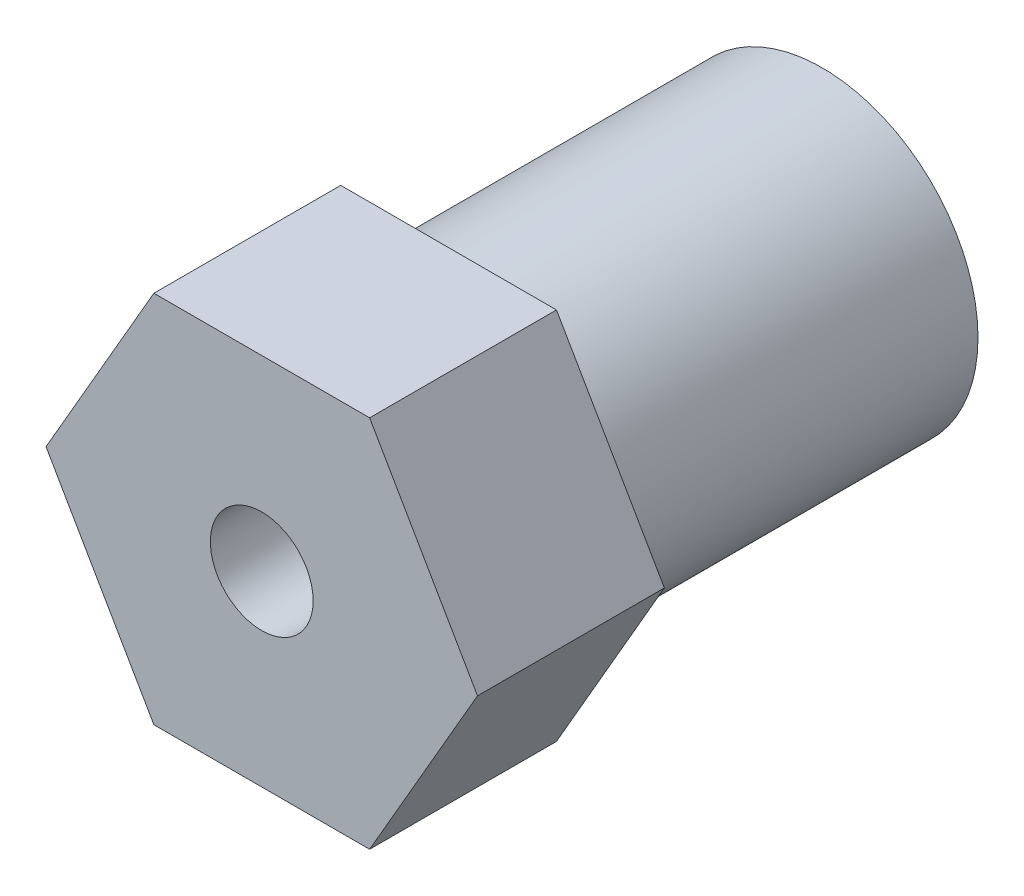
SolidWorks part; units mm, degrees
ref_plane "Front Plane" through (0, 0, 0) normal (0, 0, 1) x (1, 0, 0)
ref_plane "Top Plane" through (0, 0, 0) normal (0, 1, 0) x (1, 0, 0)
ref_plane "Right Plane" through (0, 0, 0) normal (1, 0, 0) x (0, 0, -1)
sketch "Sketch1" plane through (0, 0, 0) normal (0, 0, 1) x (1, 0, 0)
  line L1 (6.9282, 0) -> (3.4641, 6)
  line L2 (3.4641, 6) -> (-3.4641, 6)
  line L3 (-3.4641, 6) -> (-6.9282, 0)
  line L4 (-6.9282, 0) -> (-3.4641, -6)
  line L5 (-3.4641, -6) -> (3.4641, -6)
  line L6 (3.4641, -6) -> (6.9282, 0)
  circle A0 centre (0, 0) radius 6 construction
extrude "Boss-Extrude1" add sketch "Sketch1" along normal blind 6
sketch "Sketch2" plane through (0, 0, 0) normal (0, 0, 1) x (1, 0, 0)
  circle A0 centre (0, 0) radius 5
extrude "Boss-Extrude2" add sketch "Sketch2" against normal blind 12
sketch "Sketch3" plane through (0, 0, 0) normal (0, 0, 1) x (1, 0, 0)
  circle A0 centre (0, 0) radius 2.5
extrude "Cut-Extrude1" cut sketch "Sketch3" against normal blind 12
sketch "Sketch4" plane through (0, 0, 0) normal (0, 0, 1) x (1, 0, 0)
  circle A0 centre (0, 0) radius 1.65
extrude "Cut-Extrude2" cut sketch "Sketch4" along normal blind 6
sketch "Sketch5" plane through (0, 0, 0) normal (0, 1, 0) x (1, 0, 0)
  circle A0 centre (0, 9) radius 1.25
extrude "Cut-Extrude3" cut sketch "Sketch5" against normal blind 5.1
